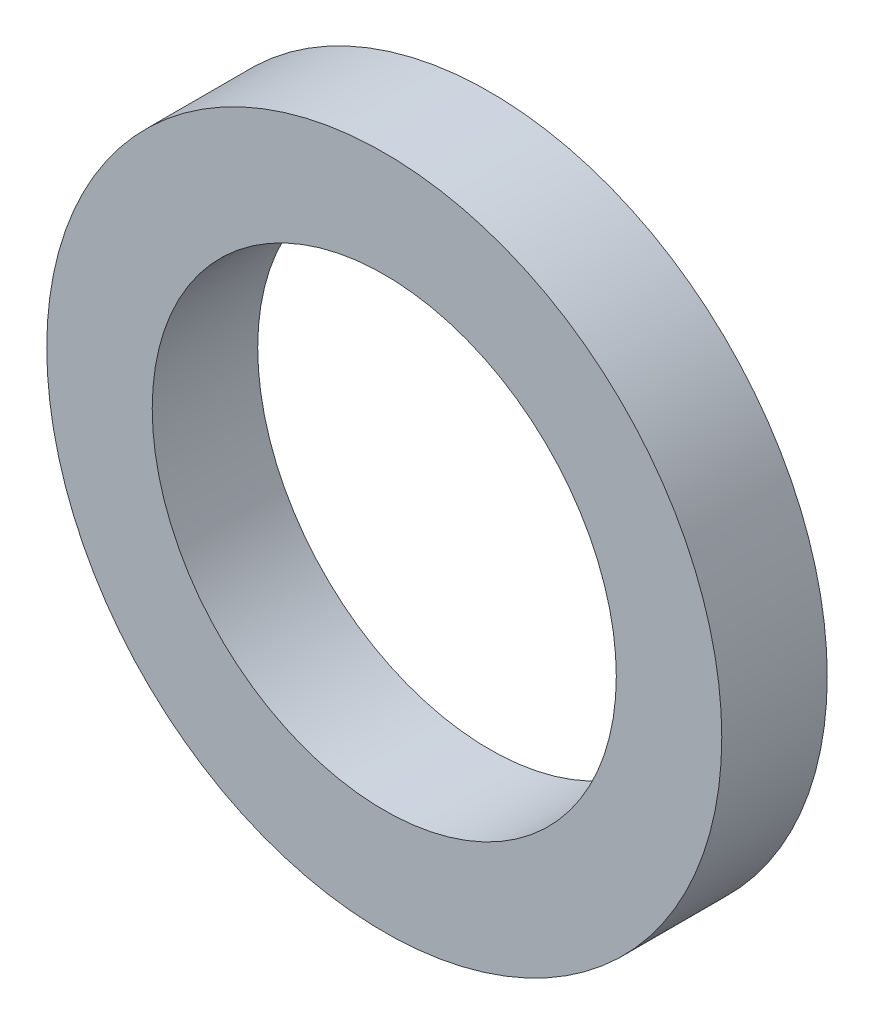
SolidWorks part; units mm, degrees
ref_plane "Front Plane" through (0, 0, 0) normal (0, 0, 1) x (1, 0, 0)
ref_plane "Top Plane" through (0, 0, 0) normal (0, 1, 0) x (1, 0, 0)
ref_plane "Right Plane" through (0, 0, 0) normal (1, 0, 0) x (0, 0, -1)
sketch "Sketch1" plane through (0, 0, 0) normal (0, 0, 1) x (1, 0, 0)
  circle A0 centre (0, 0) radius 8
  circle A1 centre (0, 0) radius 5.5
  dimension "D1" = 16
  dimension "D2" = 11
extrude "Boss-Extrude1" add sketch "Sketch1" along normal blind 2.5
